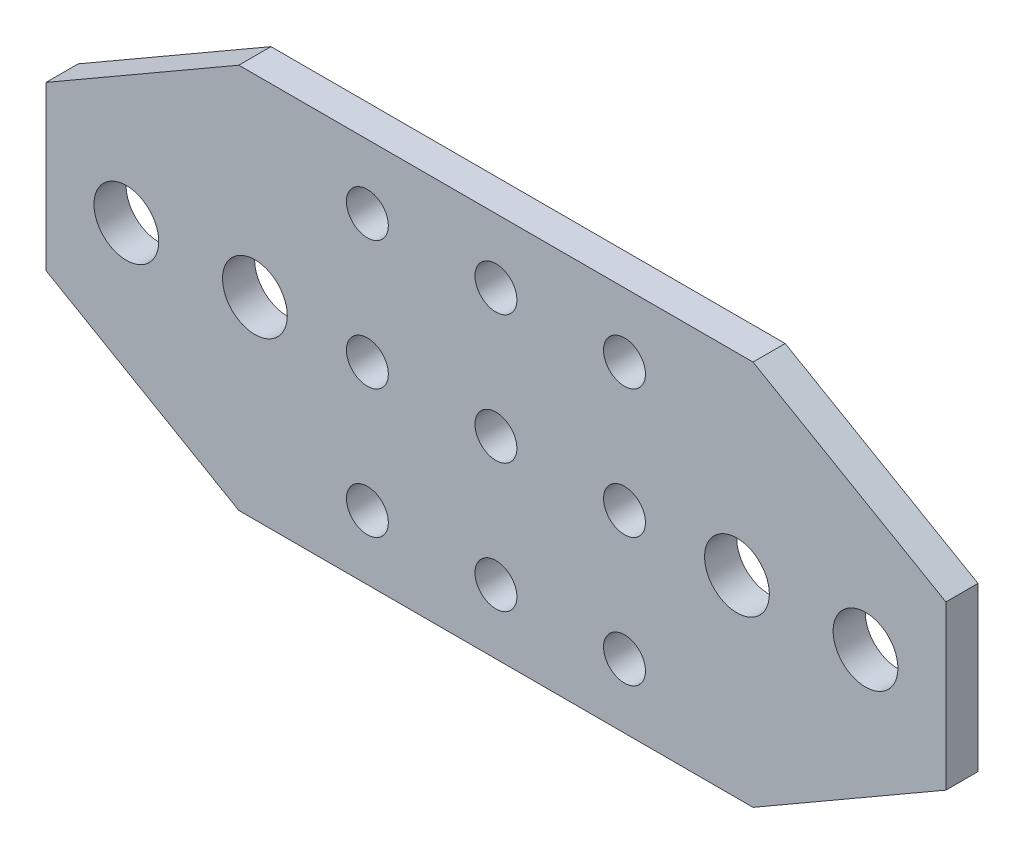
SolidWorks part; units mm, degrees
ref_plane "Front Plane" through (0, 0, 0) normal (0, 0, 1) x (1, 0, 0)
ref_plane "Top Plane" through (0, 0, 0) normal (0, 1, 0) x (1, 0, 0)
ref_plane "Right Plane" through (0, 0, 0) normal (1, 0, 0) x (0, 0, -1)
ref_plane "Plane1" through (0, 0, 0) normal (0, 0, -1) x (-1, 0, 0)
sketch "Sketch1" plane through (0, 0, 0) normal (0, 0, -1) x (-1, 0, 0)
  line L0 (44.45, -8.0515) -> (44.45, 8.0515)
  line L1 (44.45, 8.0515) -> (25.4, 19.05)
  line L2 (25.4, 19.05) -> (-25.4, 19.05)
  line L3 (-25.4, 19.05) -> (-44.45, 8.0515)
  line L4 (-44.45, 8.0515) -> (-44.45, -8.0515)
  line L5 (-44.45, -8.0515) -> (-25.4, -19.05)
  line L6 (-25.4, -19.05) -> (25.4, -19.05)
  line L7 (25.4, -19.05) -> (44.45, -8.0515)
  circle A0 centre (23.8125, 0) radius 3.2004
  circle A1 centre (0, -12.7) radius 2.0701
  circle A2 centre (0, 12.7) radius 2.0701
  circle A3 centre (0, 0) radius 2.0701
  circle A4 centre (36.5125, 0) radius 3.2004
  circle A5 centre (-12.7, -12.7) radius 2.0701
  circle A6 centre (12.7, 12.7) radius 2.0701
  circle A7 centre (12.7, -12.7) radius 2.0701
  circle A8 centre (-12.7, 12.7) radius 2.0701
  circle A9 centre (-36.5125, 0) radius 3.2004
  circle A10 centre (12.7, 0) radius 2.0701
  circle A11 centre (-12.7, 0) radius 2.0701
  circle A12 centre (-23.8125, 0) radius 3.2004
extrude "Boss-Extrude1" add sketch "Sketch1" against normal blind 3.175
